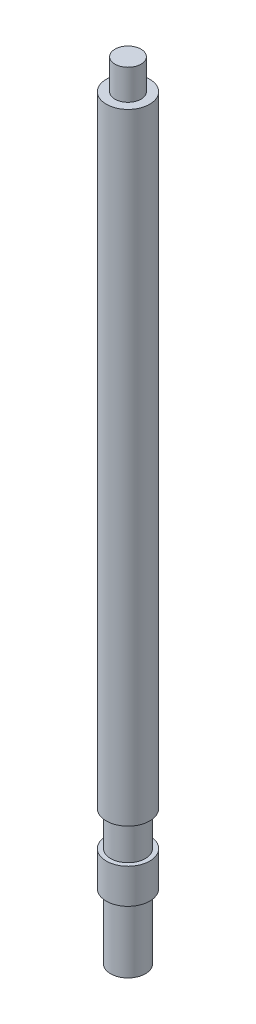
SolidWorks part; units mm, degrees
ref_plane "Front Plane" through (0, 0, 0) normal (0, 0, 1) x (1, 0, 0)
ref_plane "Top Plane" through (0, 0, 0) normal (0, 1, 0) x (1, 0, 0)
ref_plane "Right Plane" through (0, 0, 0) normal (1, 0, 0) x (0, 0, -1)
sketch "Sketch1" plane through (0, 0, 0) normal (0, 1, 0) x (1, 0, 0)
  circle A0 centre (0, 0) radius 5
  dimension "D1" = 10
extrude "Boss-Extrude1" add sketch "Sketch1" along normal blind 143
sketch "Sketch2" plane through (0, 0, 0) normal (0, -1, 0) x (1, 0, 0)
  circle A0 centre (0, 0) radius 4
  dimension "D1" = 8
extrude "Boss-Extrude2" add sketch "Sketch2" along normal blind 8 contours A0
sketch "Sketch3" plane through (0, -8, 0) normal (0, -1, 0) x (1, 0, 0)
  circle A0 centre (0, 0) radius 5
extrude "Boss-Extrude3" add sketch "Sketch3" along normal blind 8
sketch "Sketch4" plane through (0, -16, 0) normal (0, -1, 0) x (1, 0, 0)
  circle A0 centre (0, 0) radius 4
  dimension "D1" = 8
extrude "Boss-Extrude4" add sketch "Sketch4" along normal blind 15
sketch "Sketch5" plane through (0, 143, 0) normal (0, 1, 0) x (1, 0, 0)
  circle A0 centre (0, 0) radius 3
  dimension "D1" = 6
extrude "Boss-Extrude5" add sketch "Sketch5" along normal blind 7
